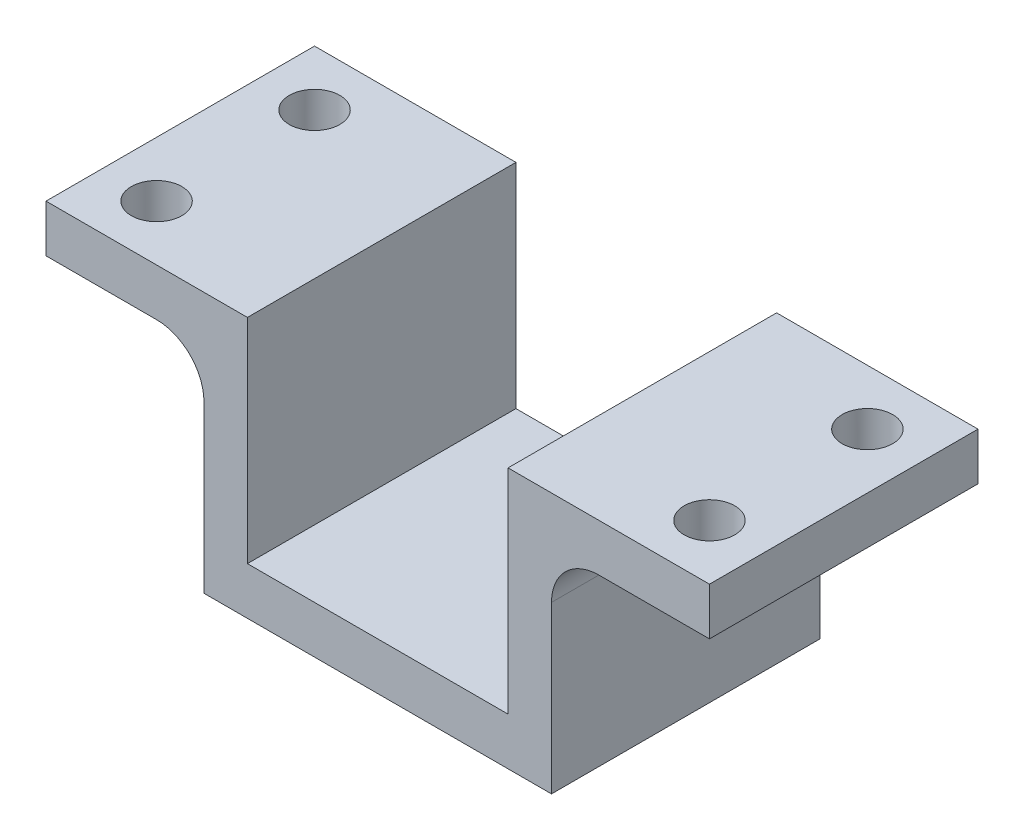
SolidWorks part; units mm, degrees
ref_plane "前视基准面" through (0, 0, 0) normal (0, 0, 1) x (1, 0, 0)
ref_plane "上视基准面" through (0, 0, 0) normal (0, 1, 0) x (1, 0, 0)
ref_plane "右视基准面" through (0, 0, 0) normal (1, 0, 0) x (0, 0, -1)
sketch "草图1" plane through (0, 0, 0) normal (0, 1, 0) x (1, 0, 0)
  line L1 (-11, -8.5) -> (11, -8.5)
  line L2 (-11, -8.5) -> (-11, 8.5)
  line L3 (-11, 8.5) -> (11, 8.5)
  line L4 (11, -8.5) -> (11, 8.5)
  line L5 (-11, -8.5) -> (11, 8.5) construction
  line L6 (-11, 8.5) -> (11, -8.5) construction
  point P0 (0, 0)
  dimension "D1" = 22
  dimension "D2" = 17
extrude "凸台-拉伸1" add sketch "草图1" along normal blind 3
sketch "草图2" plane through (0, 3, 0) normal (0, 1, 0) x (1, 0, 0)
  line L0 (0, 11.2028) -> (0, -11.3385) construction
  line L1 (-11, -8.5) -> (11, -8.5) construction
  line L2 (-11, 8.5) -> (-8.25, 8.5)
  line L3 (-11, 8.5) -> (-11, -8.5)
  line L4 (-11, -8.5) -> (-8.25, -8.5)
  line L5 (-8.25, 8.5) -> (-8.25, -8.5)
  line L6 (11, -8.5) -> (8.25, -8.5)
  line L7 (8.25, 8.5) -> (8.25, -8.5)
  line L8 (11, 8.5) -> (8.25, 8.5)
  line L9 (11, 8.5) -> (11, -8.5)
  dimension "D1" = 16.5
extrude "凸台-拉伸2" add sketch "草图2" along normal blind 13.5
sketch "草图3" plane through (0, 16.5, 0) normal (0, 1, 0) x (1, 0, 0)
  line L0 (0, 12.13) -> (0, -13.4173) construction
  line L1 (8.25, -8.5) -> (11, -8.5) construction
  line L2 (11, 8.5) -> (21, 8.5)
  line L3 (11, 8.5) -> (11, -8.5)
  line L4 (11, -8.5) -> (21, -8.5)
  line L5 (21, 8.5) -> (21, -8.5)
  line L6 (-11, -8.5) -> (-21, -8.5)
  line L7 (-21, 8.5) -> (-21, -8.5)
  line L8 (-11, 8.5) -> (-21, 8.5)
  line L9 (-11, 8.5) -> (-11, -8.5)
  dimension "D1" = 10
extrude "凸台-拉伸3" add sketch "草图3" against normal blind 3
sketch "草图4" plane through (0, 16.5, 0) normal (0, 1, 0) x (1, 0, 0)
  line L0 (0, 13.5906) -> (0, -15.1502) construction
  line L1 (-26.5336, 0) -> (27.0492, 0) construction
  circle A0 centre (-17.5, 5) radius 1.6
  circle A1 centre (-17.5, -5) radius 1.6
  circle A2 centre (17.5, -5) radius 1.6
  circle A3 centre (17.5, 5) radius 1.6
  dimension "D1" = 3.2
  dimension "D2" = 10
  dimension "D3" = 35
extrude "切除-拉伸1" cut sketch "草图4" against normal up to next
fillet "圆角1" radius 3 2 edges at (11, 13.5, 0) (-11, 13.5, 0)
